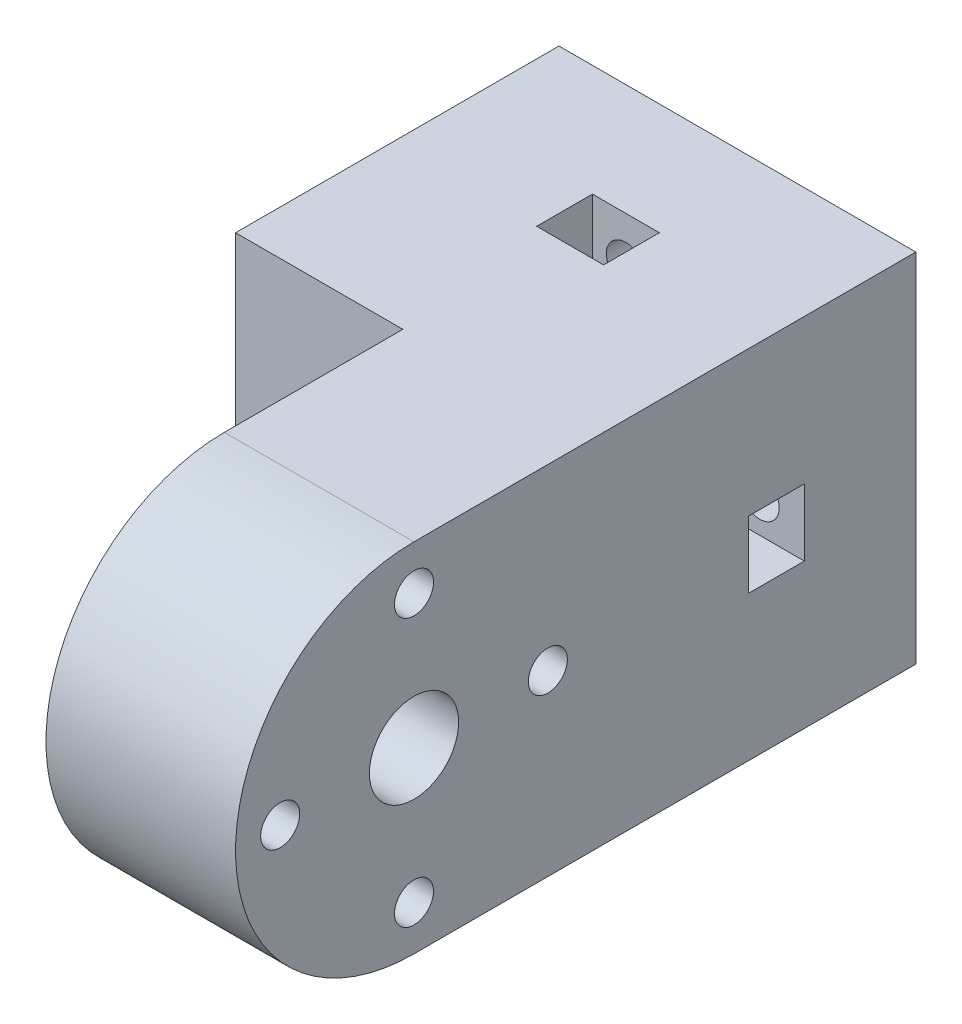
SolidWorks part; units mm, degrees
ref_plane "Front Plane" through (0, 0, 0) normal (0, 0, 1) x (1, 0, 0)
ref_plane "Top Plane" through (0, 0, 0) normal (0, 1, 0) x (1, 0, 0)
ref_plane "Right Plane" through (0, 0, 0) normal (1, 0, 0) x (0, 0, -1)
sketch "Sketch1" plane through (0, 0, 0) normal (1, 0, 0) x (0, -1, 0)
  line L1 (-16, 0) -> (16, 0)
  line L2 (-16, 0) -> (-16, 25)
  line L3 (-16, 25) -> (16, 25)
  line L4 (16, 0) -> (16, 25)
  circle A0 centre (0, 0) radius 4.5
  circle A1 centre (0, 0) radius 16
  dimension "D1" = 9
  dimension "D2" = 32
  dimension "D3" = 25
extrude "Boss-Extrude1" add sketch "Sketch1" along normal blind 32 contours A1 L4 L3 L2 | L1 A1 A0 | L1 A1 A0
sketch "Sketch4" plane through (0, 0, 0) normal (-1, 0, 0) x (0, 0, 1)
  circle A0 centre (0, 0) radius 16
  dimension "D1" = 32
extrude "Cut-Extrude3" cut sketch "Sketch4" against normal blind 15
sketch "Sketch5" plane through (15, 0, 0) normal (-1, 0, 0) x (0, 0, 1)
  circle A0 centre (0, 0) radius 7
  circle A1 centre (0, 0) radius 4
  dimension "D1" = 8
  dimension "D2" = 14
extrude "Boss-Extrude2" add sketch "Sketch5" against normal up to surface (17 mm away) up to face at (32, 0, -8.5)
sketch "Sketch15" plane through (0, 0, 0) normal (-1, 0, 0) x (0, 0, 1)
  line L0 (0, -16) -> (-25, -16) construction
  line L1 (0, 16) -> (-16, 16)
  line L2 (0, 16) -> (0, -16)
  line L3 (0, -16) -> (-16, -16)
  line L4 (-16, 16) -> (-16, -16)
  arc A0 (0, 16) -> (0, -16) centre (0, 0) ccw construction
extrude "Cut-Extrude6" cut sketch "Sketch15" against normal up to surface (15 mm away)
sketch "Sketch16" plane through (0, 0, -25) normal (0, 0, -1) x (-1, 0, 0)
  line L4 (0, -16) -> (0, 16)
  line L5 (0, 16) -> (-32, 16)
  line L6 (-32, 16) -> (-32, -16)
  line L7 (-32, -16) -> (0, -16)
  line L8 (0, -16) -> (0, 16)
  line L9 (0, 16) -> (-32, 16)
  line L10 (-32, 16) -> (-32, -16)
  line L11 (-32, -16) -> (0, -16)
  dimension "D1" = 0
extrude "Boss-Extrude6" add sketch "Sketch16" along normal blind 20
sketch "Sketch17" plane through (0, 0, -16) normal (0, 0, 1) x (1, 0, 0)
  line L0 (0, 16) -> (0, -16) construction
  line L1 (15, -16) -> (0, -16) construction
  line L2 (32, -16) -> (32, 16) construction
  line L3 (15, 16) -> (0, 16) construction
  line L4 (32, 16) -> (15, 16) construction
  circle A0 centre (4, 0) radius 1.75
  circle A1 centre (16, 12) radius 1.75
  circle A2 centre (28, 0) radius 1.75
  circle A3 centre (16, -12) radius 1.75
  dimension "D1" = 3.5
  dimension "D2" = 4
  dimension "D3" = 16
  dimension "D4" = 16
  dimension "D5" = 3.5
  dimension "D6" = 4
  dimension "D7" = 3.5
  dimension "D8" = 24
  dimension "D9" = 16
  dimension "D10" = 24
  dimension "D11" = 12
  dimension "D12" = 3.5
extrude "Cut-Extrude8" cut sketch "Sketch17" against normal through all
sketch "Sketch18" plane through (15, 0, 0) normal (-1, 0, 0) x (0, 0, 1)
  line L0 (0, 12) -> (0, 0) construction
  line L1 (0, 0) -> (0, -12) construction
  line L2 (12, 0) -> (0, 0) construction
  circle A0 centre (0, 12) radius 1.75
  circle A1 centre (0, -12) radius 1.75
  circle A2 centre (12, 0) radius 1.75
  circle A3 centre (-12, 0) radius 1.75
  dimension "D1" = 12
  dimension "D2" = 12
  dimension "D3" = 3.5
  dimension "D4" = 3.5
  dimension "D5" = 12
  dimension "D6" = 3.5
extrude "Cut-Extrude9" cut sketch "Sketch18" against normal through all
sketch "Sketch19" plane through (0, 0, -45) normal (0, 0, -1) x (-1, 0, 0)
  line L7 (0, 3) -> (-5.7321, 3)
  line L8 (-5.7321, 3) -> (-7.4641, 0)
  line L9 (-7.4641, 0) -> (-5.7321, -3)
  line L10 (-5.7321, -3) -> (0, -3)
  line L13 (-16, -8.5359) -> (-19, -10.2679)
  line L14 (-19, -10.2679) -> (-19, -16)
  line L17 (-13, -16) -> (-13, -10.2679)
  line L18 (-13, -10.2679) -> (-16, -8.5359)
  line L19 (-24.5359, 0) -> (-26.2679, 3)
  line L20 (-26.2679, 3) -> (-32, 3)
  line L23 (-32, -3) -> (-26.2679, -3)
  line L24 (-26.2679, -3) -> (-24.5359, 0)
  line L25 (0, -16) -> (0, 16) construction
  line L28 (-16, 8.5359) -> (-13, 10.2679)
  line L29 (-13, 10.2679) -> (-13, 16)
  line L31 (-32, -16) -> (0, -16)
  line L32 (0, -16) -> (0, 16)
  line L33 (0, 16) -> (-32, 16)
  line L34 (-32, 16) -> (-32, -16)
  line L35 (-19, -16) -> (-13, -16)
  line L36 (0, -3) -> (0, 3)
  line L37 (-13, 16) -> (-19, 16)
  line L38 (-32, 3) -> (-32, -3)
  line L40 (-19, 16) -> (-19, 10.2679)
  line L41 (-30.5981, 1.5) -> (-31.3919, 0.125) [skipped]
  line L42 (-30.5981, -1.5) -> (-29.8042, -2.875) [skipped]
  line L43 (-0.8815, 0.5986) -> (-1.6754, 1.9736) [skipped]
  line L44 (-1.9223, -2.4014) -> (-1.1285, -1.0264) [skipped]
  line L45 (-18.1495, -14.2231) -> (-16.7745, -15.0169) [skipped]
  line L46 (-13.8505, -14.2231) -> (-12.4755, -13.4292) [skipped]
  line L47 (-19, 10.2679) -> (-16, 8.5359)
  line L48 (-16.5986, 15.1185) -> (-17.9736, 14.3246) [skipped]
  line L49 (-13.5986, 14.0777) -> (-14.9736, 14.8715) [skipped]
  arc A0 (-19, 12) -> (-13, 12) centre (-16, 12) ccw construction
  arc A1 (-4, 3) -> (-4, -3) centre (-4, 0) ccw construction
  arc A2 (-13, -12) -> (-19, -12) centre (-16, -12) ccw construction
  arc A3 (-28, -3) -> (-28, 3) centre (-28, 0) ccw construction
  dimension "D1" = 6
  dimension "D2" = 6
  dimension "D3" = 6
  dimension "D4" = 6
  dimension "D5" = 0
extrude "Cut-Extrude10" cut sketch "Sketch19" against normal blind 5 from offset 10 offset against normal yes
sketch "Sketch20" plane through (0, 0, -45) normal (0, 0, -1) x (-1, 0, 0)
  line L0 (-28, 0) -> (-16, 0) construction
  line L1 (-16, 0) -> (-16, 12) construction
  circle A0 centre (-16, 0) radius 4.25
  dimension "D1" = 8.5
extrude "Cut-Extrude11" cut sketch "Sketch20" against normal up to surface (29 mm away) up to face at (5.75, 0, -16)
